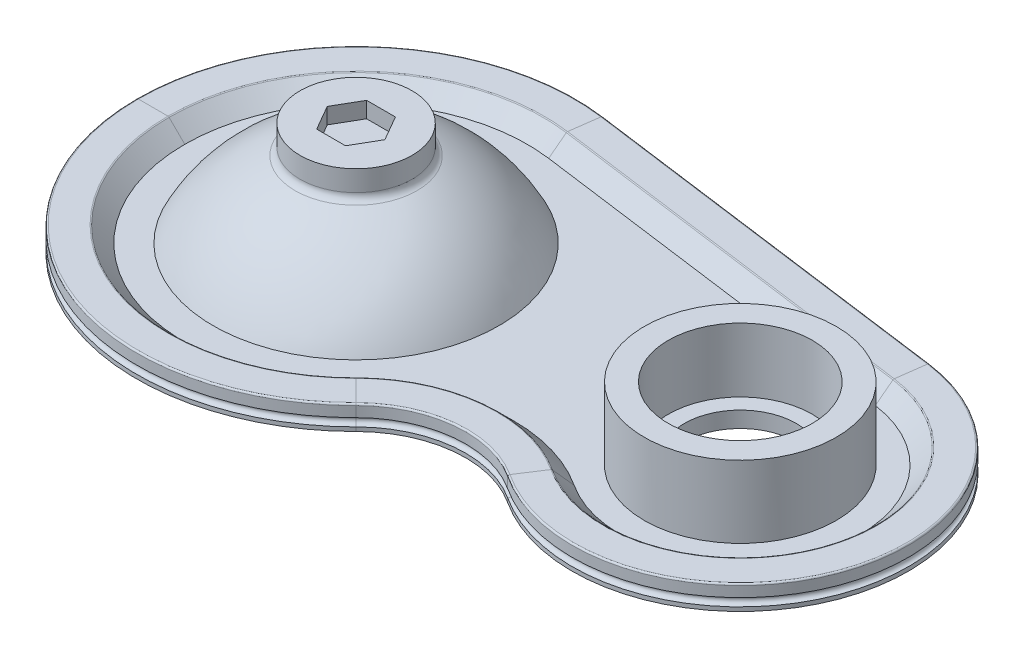
SolidWorks part; units mm, degrees
ref_plane "Front Plane" through (0, 0, 0) normal (0, 0, 1) x (1, 0, 0)
ref_plane "Top Plane" through (0, 0, 0) normal (0, 1, 0) x (1, 0, 0)
ref_plane "Right Plane" through (0, 0, 0) normal (1, 0, 0) x (0, 0, -1)
sketch "Sketch1" plane through (0, 0, 0) normal (0, 1, 0) x (1, 0, 0)
  line L0 (0, 0) -> (240, 0) construction
  line L1 (18.2667, 135.7768) -> (254, 104.0625)
  line L2 (0, 0) -> (145.2565, -145.2565) construction
  arc A0 (18.2667, 135.7768) -> (96.8736, -96.8736) centre (0, 0) ccw
  arc A1 (182.6372, -87.9461) -> (254, 104.0625) centre (240, 0) ccw
  arc A2 (182.6372, -87.9461) -> (96.8736, -96.8736) centre (145.2565, -145.2565) ccw
  dimension "D1" = 274
  dimension "D2" = 210
  dimension "D3" = 240
  dimension "D4" = 45
sketch "Sketch2" plane through (0, 0, 0) normal (0, 0, 1) x (1, 0, 0)
  line L0 (-136, 15) -> (-117.5018, 15)
  line L1 (-137, 14) -> (-137, 7.5)
  line L2 (-137, 0) -> (-107, 0)
  line L3 (-107, 5) -> (-116.7979, 14.7103)
  line L4 (-107, 0) -> (-107, 5)
  line L5 (-137, 2.5) -> (-137, 0)
  line L6 (96.8736, 0) -> (-137, 0) construction
  arc A0 (-137, 2.5) -> (-137, 7.5) centre (-137, 5) ccw
  arc A1 (-117.5018, 15) -> (-116.7979, 14.7103) centre (-117.5018, 14) cw
  arc A2 (-136, 15) -> (-137, 14) centre (-136, 14) ccw
  point P18 (-137, 15)
  dimension "D4" = 5
  dimension "D6" = 1
  dimension "D1" = 5
  dimension "D2" = 15
  dimension "D3" = 30
  dimension "D5" = 5
sweep "Sweep1" add profiles "Sketch2" path "Sketch1"
sketch "Sketch3" plane through (0, 0, 0) normal (0, 1, 0) x (1, 0, 0)
  line L3 (14.2667, 106.0446) -> (250, 74.3303) construction
  line L4 (14.2667, 106.0446) -> (250, 74.3303)
  arc A3 (199.0266, -62.8186) -> (250, 74.3303) centre (240, 0) ccw construction
  arc A4 (199.0266, -62.8186) -> (75.6604, -75.6604) centre (145.2565, -145.2565) ccw construction
  arc A5 (14.2667, 106.0446) -> (-107, 0) centre (0, 0) ccw construction
  arc A6 (-107, 0) -> (75.6604, -75.6604) centre (0, 0) ccw construction
  arc A7 (199.0266, -62.8186) -> (250, 74.3303) centre (240, 0) ccw
  arc A8 (199.0266, -62.8186) -> (75.6604, -75.6604) centre (145.2565, -145.2565) ccw
  arc A9 (14.2667, 106.0446) -> (-107, 0) centre (0, 0) ccw
  arc A10 (-107, 0) -> (75.6604, -75.6604) centre (0, 0) ccw
extrude "Boss-Extrude1" add sketch "Sketch3" along normal blind 5
sketch "Sketch4" plane through (0, 0, 0) normal (1, 0, 0) x (0, 0, -1)
  line L0 (0, 0) -> (100, 0) construction
  line L1 (60, 0) -> (60, 27.082)
  line L2 (137, 0) -> (-137, 0) construction
  line L3 (35, 70) -> (0, 70)
  line L4 (35, 70) -> (35, 57.0824)
  line L5 (0, 0) -> (0, -40) construction
  line L6 (0, 70) -> (0, 50)
  line L7 (60, 0) -> (91.6515, 0)
  arc A0 (91.6515, 0) -> (38.0952, 52.4595) centre (0, -40) ccw
  arc A1 (0, 50) -> (60, 27.082) centre (0, -40) cw
  arc A2 (35, 57.0824) -> (38.0952, 52.4595) centre (40, 57.0824) ccw
  dimension "D1" = 40
  dimension "D2" = 90
  dimension "D5" = 100
  dimension "D7" = 5
  dimension "D3" = 60
  dimension "D4" = 35
  dimension "D6" = 70
revolve "Revolve1" add sketch "Sketch4" angle 360 about L6
sketch "Sketch5" plane through (0, 5, 0) normal (0, 1, 0) x (1, 0, 0)
  circle A1 centre (0, 0) radius 60
  circle A2 centre (0, 0) radius 60
  dimension "D1" = 0
extrude "Cut-Extrude1" cut sketch "Sketch5" against normal up to next
sketch "Sketch6" plane through (0, 70, 0) normal (0, 1, 0) x (1, 0, 0)
  line L0 (0, 0) -> (240, 0) construction
  line L1 (-18, 0) -> (-9, -15.5885)
  line L2 (-9, -15.5885) -> (9, -15.5885)
  line L3 (9, -15.5885) -> (18, 0)
  line L4 (18, 0) -> (9, 15.5885)
  line L5 (9, 15.5885) -> (-9, 15.5885)
  line L6 (-9, 15.5885) -> (-18, 0)
  circle A0 centre (0, 0) radius 18 construction
  dimension "D1" = 36
extrude "Cut-Extrude2" cut sketch "Sketch6" against normal blind 10
sketch "Sketch7" plane through (0, 60, 0) normal (0, 1, 0) x (1, 0, 0)
  circle A0 centre (0, 0) radius 18
  dimension "D1" = 36
ref_plane "Plane1" through (240, 0, 0) normal (1, 0, 0) x (0, 0, -1)
sketch "Sketch8" plane through (240, 0, 0) normal (1, 0, 0) x (0, 0, -1)
  line L0 (60, 0) -> (60, 50)
  line L1 (137, 0) -> (-137, 0) construction
  line L2 (45, 50) -> (45, 10)
  line L3 (45, 10) -> (35, 10)
  line L4 (35, 10) -> (35, 0)
  line L5 (35, 0) -> (60, 0)
  line L6 (45, 50) -> (60, 50)
  line L7 (0, 0) -> (0, 49.2585) construction
  dimension "D1" = 35
  dimension "D2" = 40
  dimension "D3" = 50
  dimension "D4" = 45
  dimension "D5" = 60
revolve "Revolve2" add sketch "Sketch8" angle 360 about L7
sketch "Sketch10" plane through (0, 5, 0) normal (0, 1, 0) x (1, 0, 0)
  circle A1 centre (240, 0) radius 35
  circle A2 centre (240, 0) radius 35
  dimension "D1" = 0
extrude "Cut-Extrude3" cut sketch "Sketch10" against normal through all
